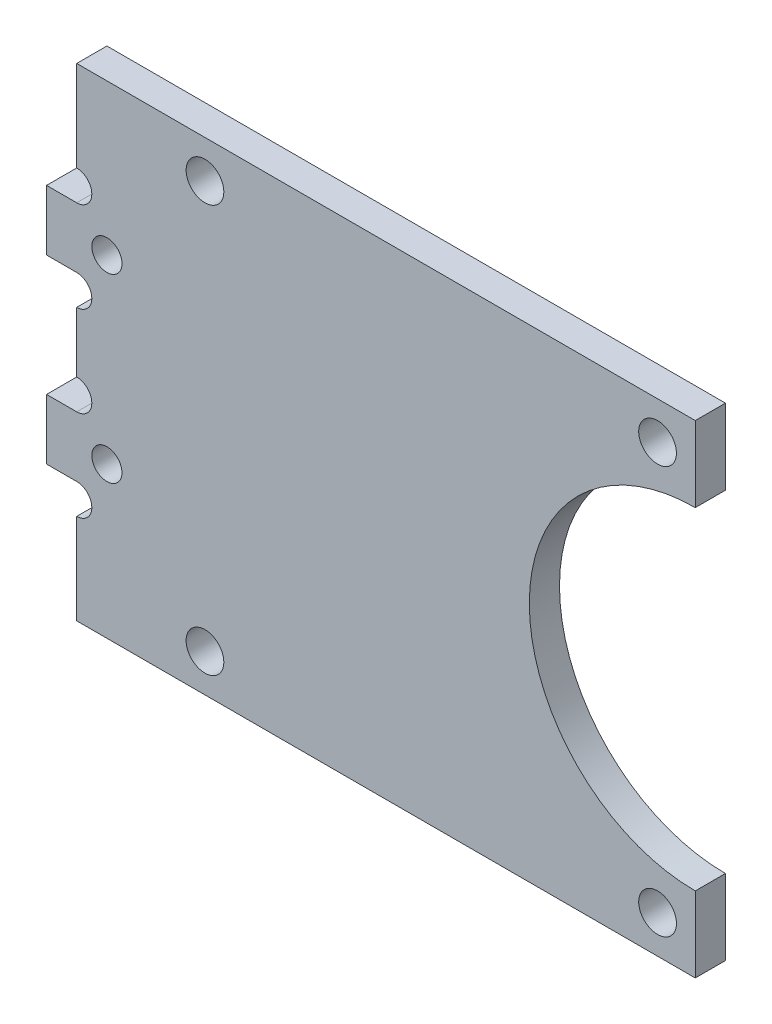
SolidWorks part; units mm, degrees
material "自訂玻璃纖維"
ref_plane "前基準面" through (0, 0, 0) normal (0, 0, 1) x (1, 0, 0)
ref_plane "上基準面" through (0, 0, 0) normal (0, 1, 0) x (1, 0, 0)
ref_plane "右基準面" through (0, 0, 0) normal (1, 0, 0) x (0, 0, -1)
sketch "草圖1" plane through (0, 0, 0) normal (0, 0, 1) x (1, 0, 0)
  line L0 (-17.2162, 10.1625) -> (15.2838, 10.1625)
  line L1 (15.2838, 10.1625) -> (15.2838, -21.8375)
  line L2 (15.2838, -21.8375) -> (-17.2162, -21.8375)
  line L3 (-25.7162, -3.8375) -> (-25.7162, -7.8375)
  line L4 (-25.7162, 2.1625) -> (-27.7162, 2.1625)
  line L5 (-17.2162, 10.1625) -> (-19.7162, 10.1625)
  line L6 (-27.7162, -9.8375) -> (-27.7162, -13.8375)
  line L7 (-17.2162, -21.8375) -> (-19.7162, -21.8375)
  line L8 (-25.7162, -1.8375) -> (-27.7162, -1.8375)
  line L9 (-19.7162, 10.1625) -> (-25.7162, 10.1625)
  line L10 (-27.7162, 2.1625) -> (-27.7162, -1.8375)
  line L11 (-19.7162, -21.8375) -> (-25.7162, -21.8375)
  line L12 (-25.7162, 10.1625) -> (-25.7162, 4.1625)
  line L13 (-25.7162, -9.8375) -> (-27.7162, -9.8375)
  line L14 (-25.7162, -13.8375) -> (-27.7162, -13.8375)
  line L15 (-25.7162, -15.8375) -> (-25.7162, -21.8375)
  circle A0 centre (-17.2162, 7.6625) radius 1.25
  circle A1 centre (-17.2162, -19.3375) radius 1.25
  circle A2 centre (12.7838, -19.3375) radius 1.25
  circle A3 centre (12.7838, 7.6625) radius 1.25
  circle A4 centre (-23.7162, -11.8375) radius 1
  circle A5 centre (-23.7162, 0.1625) radius 1
  arc A6 (-25.7162, 2.1625) -> (-25.7162, 4.1625) centre (-25.7162, 3.1625) ccw
  arc A7 (-25.7162, -1.8375) -> (-25.7162, -3.8375) centre (-25.7162, -2.8375) cw
  arc A8 (-25.7162, -13.8375) -> (-25.7162, -15.8375) centre (-25.7162, -14.8375) cw
  arc A9 (-25.7162, -9.8375) -> (-25.7162, -7.8375) centre (-25.7162, -8.8375) ccw
  dimension "D7" = 2
  dimension "D8" = 4
  dimension "D9" = 2
  dimension "D10" = 2
  dimension "D4" = 2.5
  dimension "D5" = 30
  dimension "D6" = 12
  dimension "D2" = 2.5
  dimension "D3" = 35
  dimension "D11" = 6
extrude "填料-伸長1" add sketch "草圖1" along normal blind 2
sketch "草圖4" plane through (0, 0, 0) normal (0, 0, -1) x (-1, 0, 0)
  line L1 (-15.2838, -21.8375) -> (-15.2838, 10.1625) construction
  line L4 (-15.2838, -16.8375) -> (-15.2838, 5.1625)
  arc A2 (-15.2838, 5.1625) -> (-15.2838, -16.8375) centre (-15.2838, -5.8375) cw
extrude "除料-伸長1" cut sketch "草圖4" against normal blind 2
